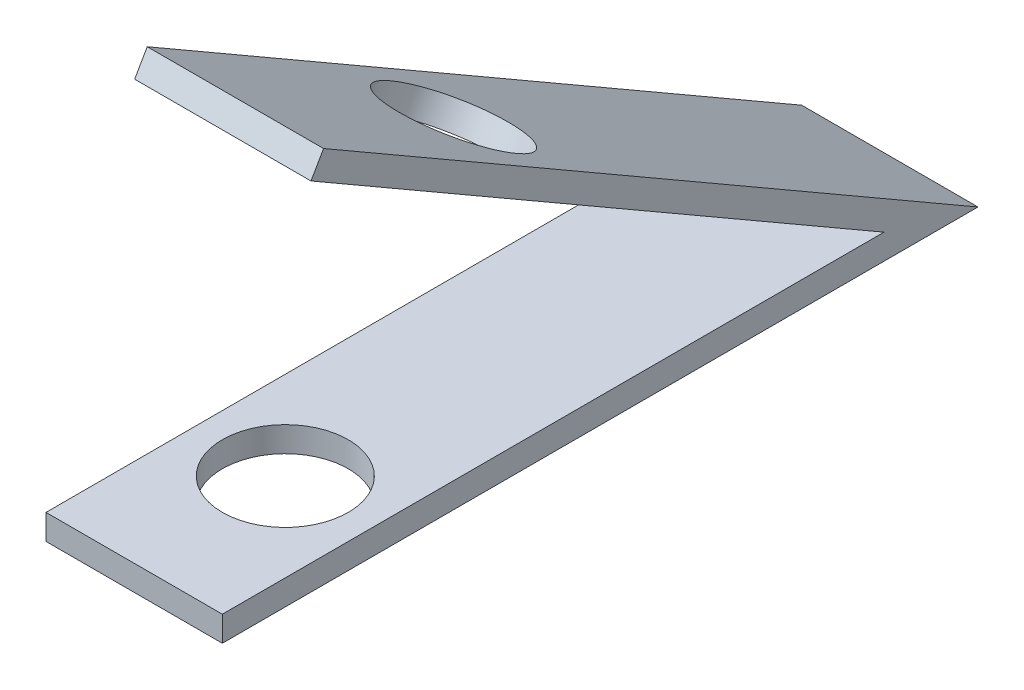
SolidWorks part; units mm, degrees
ref_plane "Front Plane" through (0, 0, 0) normal (0, 0, 1) x (1, 0, 0)
ref_plane "Top Plane" through (0, 0, 0) normal (0, 1, 0) x (1, 0, 0)
ref_plane "Right Plane" through (0, 0, 0) normal (1, 0, 0) x (0, 0, -1)
sketch "Sketch1" plane through (0, 0, 0) normal (1, 0, 0) x (0, 0, -1)
  line L0 (-227.4871, 131.3397) -> (0, 0)
  line L1 (0, 0) -> (-262.6795, 0)
  line L2 (-262.6795, 0) -> (-262.6795, -10)
  line L3 (-262.6795, -10) -> (37.3205, -10)
  line L4 (37.3205, -10) -> (-222.4871, 140)
  line L5 (-222.4871, 140) -> (-227.4871, 131.3397)
  dimension "D1" = 10
  dimension "D2" = 10
  dimension "D3" = 300
  dimension "D4" = 300
  dimension "D5" = 30
extrude "Boss-Extrude1" add sketch "Sketch1" along normal blind 70
sketch "Sketch2" plane through (0, 8.6603, -5) normal (0, 0.866, -0.5) x (1, 0, 0)
  line L0 (0, 37.3205) -> (0, -262.6795) construction
  line L4 (70, -262.6795) -> (0, -262.6795) construction
  circle A0 centre (35, -162.6795) radius 25
  dimension "D1" = 50
  dimension "D2" = 35
  dimension "D3" = 100
extrude "Cut-Extrude1" cut sketch "Sketch2" against normal blind 10
sketch "Sketch5" plane through (0, 0, 0) normal (0, 1, 0) x (1, 0, 0)
  line L0 (70, -262.6795) -> (0, -262.6795) construction
  line L1 (70, 37.3205) -> (70, -222.4871) construction
  circle A0 centre (35, -202.6795) radius 25
  dimension "D1" = 50
  dimension "D2" = 60
  dimension "D3" = 35
extrude "Cut-Extrude3" cut sketch "Sketch5" against normal blind 300
equation "\"mountAngle\" = 30deg"
equation "\"D5@Sketch1\"=\"mountAngle\""
equation "\"ThrusterDim\"= 140mm"
equation "\"hatchHoleDiameter\"= 600mm"
equation "\"hullThickness\"= 120mm"
equation "\"gasketHullInterconnectWidth\"= 100mm"
equation "\"collarThickness\"= 15"
equation "\"hatchTunnelLength\"=200"
equation "\"oRingDiameter\"=2"
equation "\"boltPatternRadiusInterconnect\"=500"
equation "\"interconnectBoltDiameter\"=30"
equation "\"hatchShaftDiameter\"=20"
equation "\"hatchMinima\"=50"
equation "\"hullDiameter\"=2000"
equation "\"hatchMaxima\"=180"
equation "\"bushingFlatHatch\"=15"
equation "\"hingePivotDiameter\"=20"
equation "\"handleWidth\"=250"
equation "\"handleHeight\"=160"
equation "\"handleThickness\"=25"
equation "\"FrameLength\"= 4300"
equation "\"FrameMidLength\"= 3000"
equation "\"TubeOD\"= 100"
equation "\"FrameBackFlat\"= 800"
equation "\"TubeWall\"=15"
equation "\"TopMemberAngle\"=120"
equation "\"FrameHight\"= 2500"
